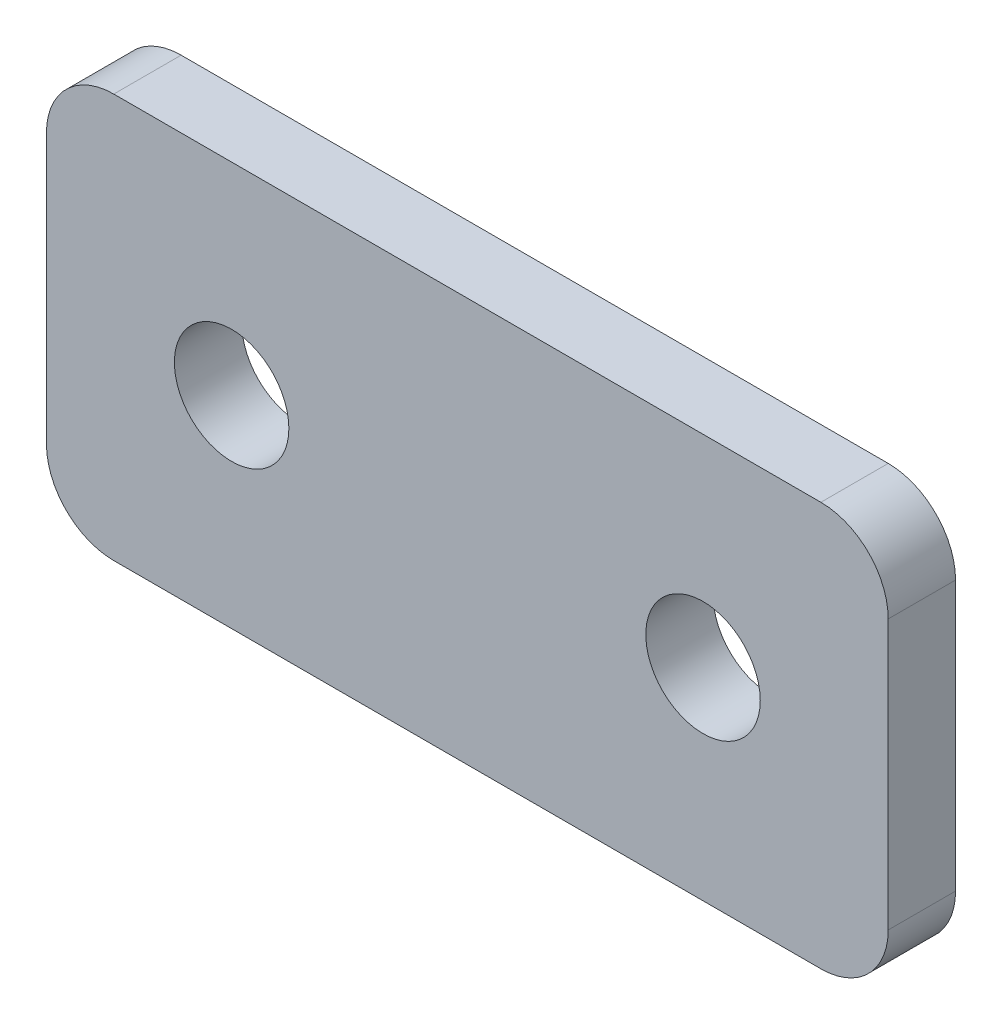
SolidWorks part; units mm, degrees
material "AISI 1020"
ref_plane "Front Plane" through (0, 0, 0) normal (0, 0, 1) x (1, 0, 0)
ref_plane "Top Plane" through (0, 0, 0) normal (0, 1, 0) x (1, 0, 0)
ref_plane "Right Plane" through (0, 0, 0) normal (1, 0, 0) x (0, 0, -1)
sketch "Sketch1" plane through (0, 0, 0) normal (0, 0, 1) x (1, 0, 0)
  line L1 (-12.5, -6) -> (12.5, -6)
  line L2 (-12.5, -6) -> (-12.5, 6)
  line L3 (-12.5, 6) -> (12.5, 6)
  line L4 (12.5, -6) -> (12.5, 6)
  line L5 (-12.5, -6) -> (12.5, 6) construction
  line L6 (-12.5, 6) -> (12.5, -6) construction
  point P0 (0, 0)
  dimension "D1" = 12
  dimension "D2" = 25
extrude "Boss-Extrude1" add sketch "Sketch1" along normal blind 2
hole_wizard "M3 Clearance Hole1" positions "Sketch2" profile "Sketch3" hole size "M3" standard "ANSI Metric" end condition through all
sketch "Sketch2" plane through (0, 0, 2) normal (0, 0, 1) x (1, 0, 0)
  point P0 (-7, 0)
  point P2 (7, 0)
  point P11 (6.6528, 1)
  point P13 (0, 0)
  point P14 (0, 0)
  dimension "D1" = 7
  dimension "D2" = 7
sketch "Sketch3" plane through (-7, 0, 2) normal (1, 0, 0) x (0, -1, 0)
  line L0 (0, 0) -> (0, 2)
  line L1 (0, 2) -> (1.7, 2)
  line L2 (1.7, 2) -> (1.7, 0)
  line L5 (1.7, 0) -> (0, 0)
  line L11 (0, -6.35) -> (0, 107.95) construction
  dimension "Thru Hole Dia." = 3.4
  dimension "Thru Hole Depth" = 2
sketch "Sketch4" plane through (0, -6, 0) normal (0, -1, 0) x (1, 0, 0)
  line L0 (-12.5, 2) -> (12.5, 2) construction
  line L1 (16.6361, 0) -> (-17.8659, 0)
  line L2 (16.6361, 0) -> (16.6361, 2)
  line L3 (16.6361, 2) -> (-17.8659, 2)
  line L4 (-17.8659, 0) -> (-17.8659, 2)
  line L5 (-12.5, 0) -> (12.5, 0) construction
fillet "Fillet1" radius 2 4 edges at (-12.5, 6, 1) (-12.5, -6, 1) (12.5, -6, 1) (12.5, 6, 1)
